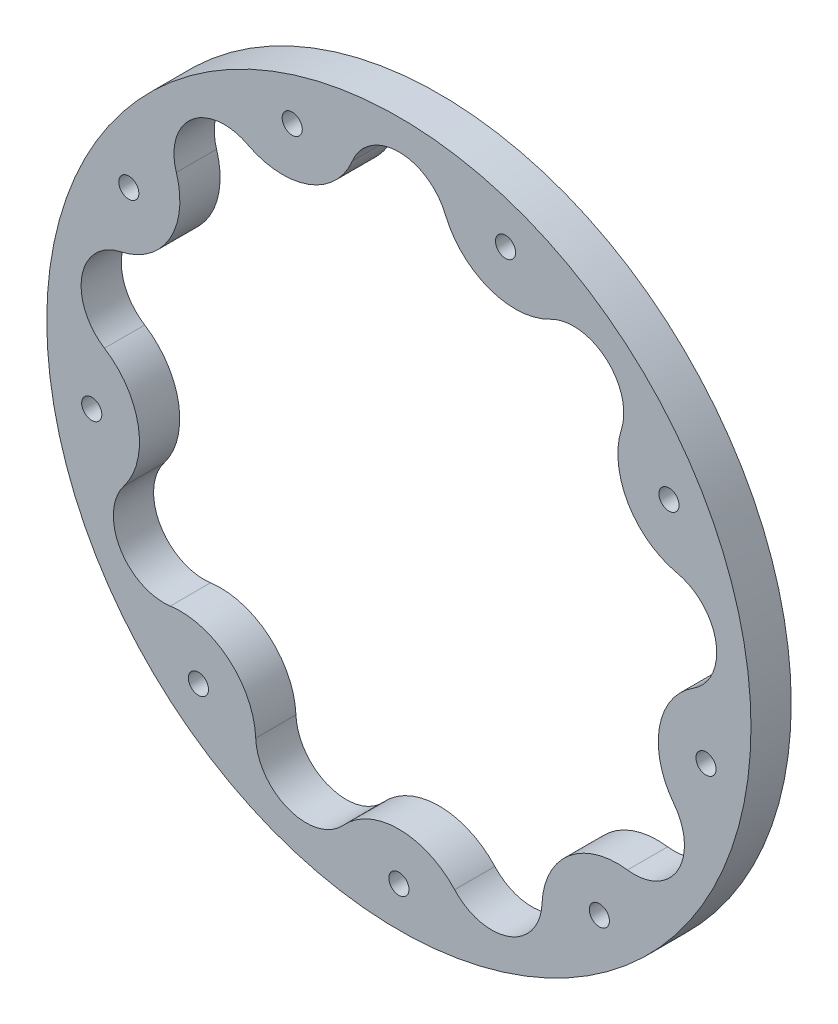
SolidWorks part; units mm, degrees
ref_plane "前视基准面" through (0, 0, 0) normal (0, 0, 1) x (1, 0, 0)
ref_plane "上视基准面" through (0, 0, 0) normal (0, 1, 0) x (1, 0, 0)
ref_plane "右视基准面" through (0, 0, 0) normal (1, 0, 0) x (0, 0, -1)
other "Configuration Table"
sketch "草图1" plane through (0, 0, 0) normal (0, 0, 1) x (1, 0, 0)
  circle A0 centre (0, 0) radius 70
  dimension "D1" = 140
extrude "凸台-拉伸1" add sketch "草图1" along normal blind 8
sketch "草图2" plane through (0, 0, 8) normal (0, 0, 1) x (1, 0, 0)
  arc A0 (9.2472, 57.8065) -> (-9.2472, 57.8065) centre (0, 54) ccw
  arc A1 (44.2411, 38.3383) -> (30.0735, 50.2263) centre (34.7105, 41.3664) ccw
  arc A2 (58.534, 0.9313) -> (55.3225, 19.1447) centre (53.1796, 9.377) ccw
  arc A3 (45.4383, -36.9115) -> (54.6855, -20.8949) centre (46.7654, -27) ccw
  arc A4 (11.0815, -57.483) -> (28.4605, -51.1576) centre (18.4691, -50.7434) ccw
  arc A5 (-28.4605, -51.1576) -> (-11.0815, -57.483) centre (-18.4691, -50.7434) ccw
  arc A6 (-54.6855, -20.8949) -> (-45.4383, -36.9115) centre (-46.7654, -27) ccw
  arc A7 (-55.3225, 19.1447) -> (-58.534, 0.9313) centre (-53.1796, 9.377) ccw
  arc A8 (-30.0735, 50.2263) -> (-44.2411, 38.3383) centre (-34.7105, 41.3664) ccw
  arc A9 (-30.0735, 50.2263) -> (-9.2472, 57.8065) centre (-23.118, 63.5162) ccw
  arc A10 (9.2472, 57.8065) -> (30.0735, 50.2263) centre (23.118, 63.5162) ccw
  arc A11 (44.2411, 38.3383) -> (55.3225, 19.1447) centre (58.5368, 33.7963) ccw
  arc A12 (58.534, 0.9313) -> (54.6855, -20.8949) centre (66.5656, -11.7373) ccw
  arc A13 (45.4383, -36.9115) -> (28.4605, -51.1576) centre (43.4476, -51.7789) ccw
  arc A14 (11.0815, -57.483) -> (-11.0815, -57.483) centre (0, -67.5925) ccw
  arc A15 (-28.4605, -51.1576) -> (-45.4383, -36.9115) centre (-43.4476, -51.7789) ccw
  arc A16 (-54.6855, -20.8949) -> (-58.534, 0.9313) centre (-66.5656, -11.7373) ccw
  arc A17 (-55.3225, 19.1447) -> (-44.2411, 38.3383) centre (-58.5368, 33.7963) ccw
  point P21 (0, 0)
  dimension "D1" = 20
  dimension "D4" = 9
  dimension "D2" = 54
  dimension "D3" = 9
extrude "切除-拉伸1" cut sketch "草图2" against normal blind 8
sketch "草图3" plane through (0, 0, 0) normal (0, 0, -1) x (-1, 0, 0)
  line L0 (0, 0) -> (0, 104.3066) construction
  line L1 (0, 0) -> (21.2052, 58.2609) construction
  circle A0 centre (0, 0) radius 62 construction
  circle A1 centre (21.2052, 58.2609) radius 2
  circle A2 centre (53.6936, 31) radius 2
  circle A3 centre (61.0581, -10.7662) radius 2
  circle A4 centre (39.8528, -47.4948) radius 2
  circle A5 centre (0, -62) radius 2
  circle A6 centre (-39.8528, -47.4948) radius 2
  circle A7 centre (-61.0581, -10.7662) radius 2
  circle A8 centre (-53.6936, 31) radius 2
  circle A9 centre (-21.2052, 58.2609) radius 2
  point P24 (0, 0)
  dimension "D1" = 124
  dimension "D2" = 20
  dimension "D3" = 4
  dimension "D4" = 9
extrude "切除-拉伸2" cut sketch "草图3" against normal blind 8
